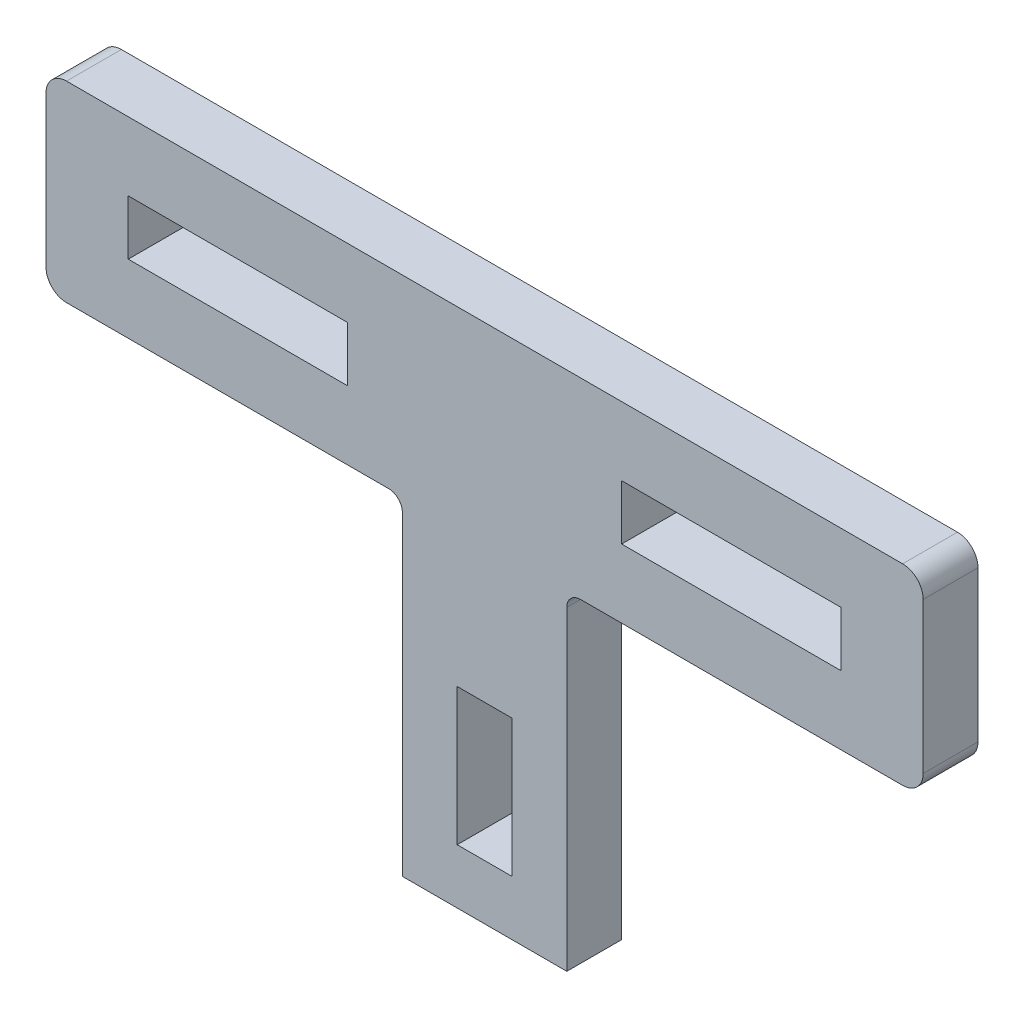
SolidWorks part; units mm, degrees
ref_plane "Front Plane" through (0, 0, 0) normal (0, 0, 1) x (1, 0, 0)
ref_plane "Top Plane" through (0, 0, 0) normal (0, 1, 0) x (1, 0, 0)
ref_plane "Right Plane" through (0, 0, 0) normal (1, 0, 0) x (0, 0, -1)
sketch "Sketch1" plane through (0, 0, 0) normal (0, 0, 1) x (1, 0, 0)
  line L0 (0, 3.5) -> (0, 0) construction
  line L1 (15.25, 3.5) -> (-15.25, 3.5)
  line L2 (15.25, -3.5) -> (3.5, -3.5)
  line L3 (3, -4) -> (3, -15.5)
  line L4 (16, 2.75) -> (16, -2.75)
  line L5 (0, 0) -> (16, 0) construction
  line L6 (0, 0) -> (0, 10.3379) construction
  line L7 (0, 0) -> (0, -8.6712) construction
  line L8 (3, -15.5) -> (-3, -15.5)
  line L9 (-13, 1) -> (-13, -1)
  line L10 (-5, 1) -> (-13, 1)
  line L11 (5, 1) -> (13, 1)
  line L12 (5, 1) -> (5, -1)
  line L13 (5, -1) -> (13, -1)
  line L14 (13, 1) -> (13, -1)
  line L15 (-5, 1) -> (-5, -1)
  line L16 (-5, -1) -> (-13, -1)
  line L17 (-3, -4) -> (-3, -15.5)
  line L18 (-15.25, -3.5) -> (-3.5, -3.5)
  line L19 (-16, 2.75) -> (-16, -2.75)
  line L20 (-5.075, 0.925) -> (-12.925, 0.925) construction
  line L21 (-1, -8.5) -> (1, -8.5)
  line L22 (-1, -8.5) -> (-1, -13.5)
  line L23 (-1, -13.5) -> (1, -13.5)
  line L24 (1, -8.5) -> (1, -13.5)
  line L25 (-12.925, 0.925) -> (-12.925, -0.925) construction
  line L26 (-5.075, -0.925) -> (-12.925, -0.925) construction
  line L27 (-5.075, 0.925) -> (-5.075, -0.925) construction
  line L28 (5.075, 0.925) -> (12.925, 0.925) construction
  line L29 (12.925, 0.925) -> (12.925, -0.925) construction
  line L30 (5.075, -0.925) -> (12.925, -0.925) construction
  line L31 (5.075, 0.925) -> (5.075, -0.925) construction
  line L32 (-0.925, -8.575) -> (0.925, -8.575) construction
  line L33 (0.925, -8.575) -> (0.925, -13.425) construction
  line L34 (-0.925, -13.425) -> (0.925, -13.425) construction
  line L35 (-0.925, -8.575) -> (-0.925, -13.425) construction
  arc A0 (-15.25, -3.5) -> (-16, -2.75) centre (-15.25, -2.75) cw
  arc A1 (-16, 2.75) -> (-15.25, 3.5) centre (-15.25, 2.75) cw
  arc A2 (15.25, -3.5) -> (16, -2.75) centre (15.25, -2.75) ccw
  arc A3 (15.25, 3.5) -> (16, 2.75) centre (15.25, 2.75) cw
  arc A4 (3.5, -3.5) -> (3, -4) centre (3.5, -4) ccw
  arc A5 (-3, -4) -> (-3.5, -3.5) centre (-3.5, -4) ccw
  point P20 (0, -15.5)
  point P29 (-16, -3.5)
  point P32 (-16, 3.5)
  point P35 (16, -3.5)
  point P38 (16, 3.5)
  point P41 (3, -3.5)
  point P44 (-3, -3.5)
  dimension "D13" = 0.75
  dimension "D14" = 0.5
  dimension "D1" = 2.5
  dimension "D2" = 16
  dimension "D3" = 5
  dimension "D4" = 8
  dimension "D5" = 1
  dimension "D6" = 2
  dimension "D7" = 3
  dimension "D8" = 12
  dimension "D9" = 2
  dimension "D10" = 5
  dimension "D11" = 2
  dimension "D12" = 1
  dimension "D17" = 0.075
  dimension "D15" = 0.075
  dimension "D16" = 0.075
extrude "Boss-Extrude1" add sketch "Sketch1" along normal blind 2
